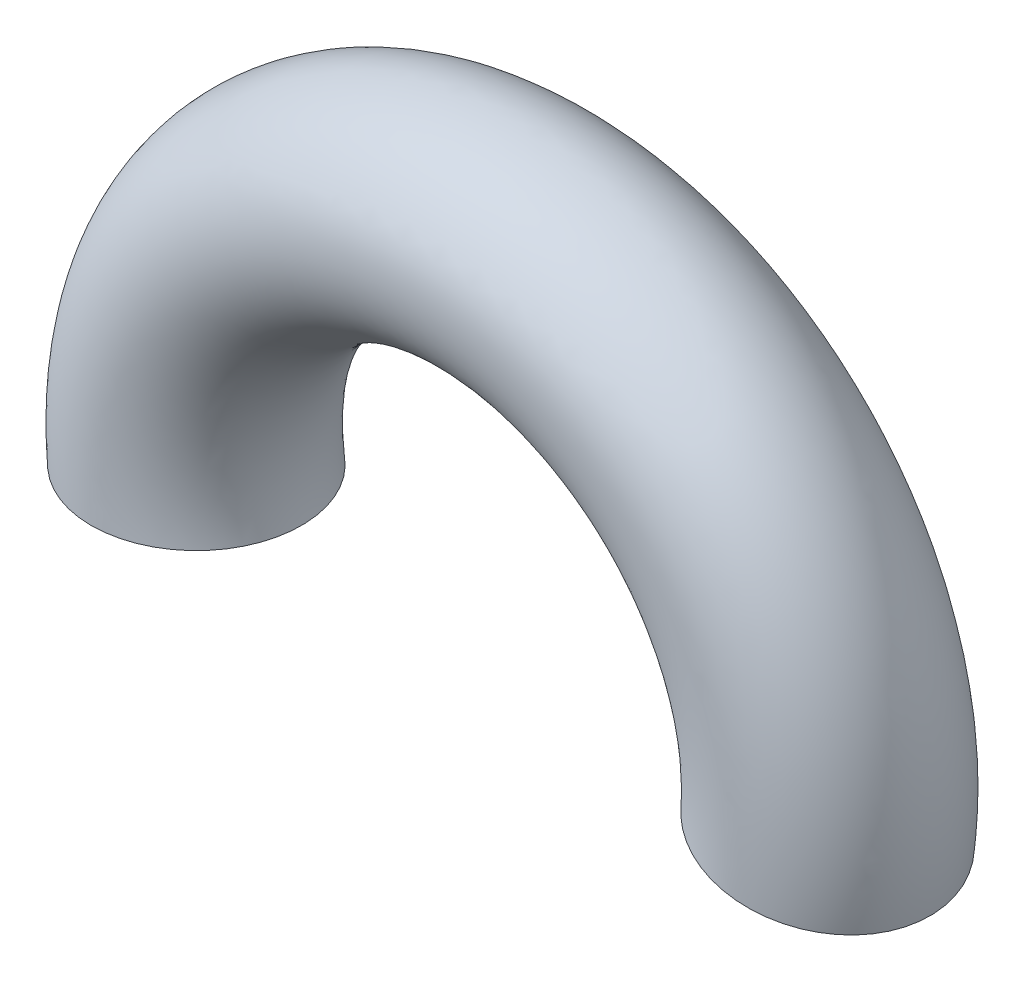
SolidWorks part; units mm, degrees
ref_plane "Alzado" through (0, 0, 0) normal (0, 0, 1) x (1, 0, 0)
ref_plane "Planta" through (0, 0, 0) normal (0, 1, 0) x (1, 0, 0)
ref_plane "Vista lateral" through (0, 0, 0) normal (1, 0, 0) x (0, 0, -1)
sketch "Sketch1" plane through (0, 0, 0) normal (0, 1, 0) x (1, 0, 0)
  line L0 (0, 0) -> (0, 9.4179) construction
  circle A0 centre (-7, 0) radius 2
  point P5 (5, 0)
  dimension "D1" = 4
  dimension "D2" = 7
  dimension "D3" = 5
sketch3d "3DSketch1"
  arc A0 (-7, 0, 0) -> (5, 0, 0) centre (-1, 0.6896, 0) cw
  point P2 (-1, 0.6896, -6.0395)
sweep "Sweep1" add profiles "Sketch1" path "3DSketch1"
